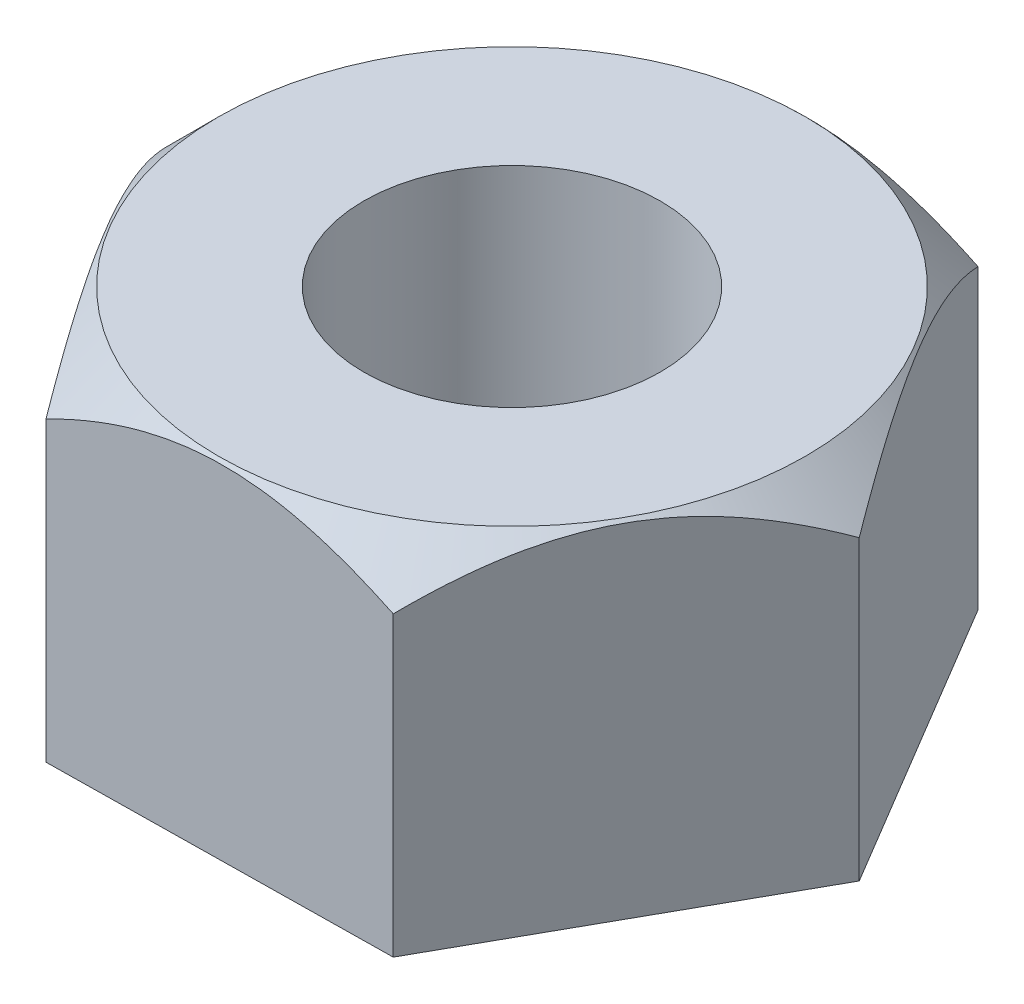
SolidWorks part; units mm, degrees
ref_plane "Front Plane" through (0, 0, 0) normal (0, 0, 1) x (1, 0, 0)
ref_plane "Top Plane" through (0, 0, 0) normal (0, 1, 0) x (1, 0, 0)
ref_plane "Right Plane" through (0, 0, 0) normal (1, 0, 0) x (0, 0, -1)
sketch "Sketch1" plane through (0, 0, 0) normal (0, 1, 0) x (1, 0, 0)
  line L1 (17.7411, -29.7532) -> (34.6376, 0.4876)
  line L2 (34.6376, 0.4876) -> (16.8965, 30.2408)
  line L3 (16.8965, 30.2408) -> (-17.7411, 29.7532)
  line L4 (-17.7411, 29.7532) -> (-34.6376, -0.4876)
  line L5 (-34.6376, -0.4876) -> (-16.8965, -30.2408)
  line L6 (-16.8965, -30.2408) -> (17.7411, -29.7532)
  circle A0 centre (0, 0) radius 30 construction
  dimension "D1" = 60
extrude "Boss-Extrude1" add sketch "Sketch1" along normal blind 35
sketch "Sketch2" plane through (0, 35, 0) normal (0, 1, 0) x (1, 0, 0)
  circle A0 centre (0, 0) radius 15
  dimension "D1" = 30
extrude "Cut-Extrude1" cut sketch "Sketch2" against normal through all
sketch "Sketch6" plane through (0, 35, 0) normal (0, 1, 0) x (1, 0, 0)
  circle A0 centre (0, 0) radius 29.7145
  dimension "D1" = 29.7145
extrude "Cut-Extrude5" cut sketch "Sketch6" against normal blind 10 draft 45 flip side to cut
